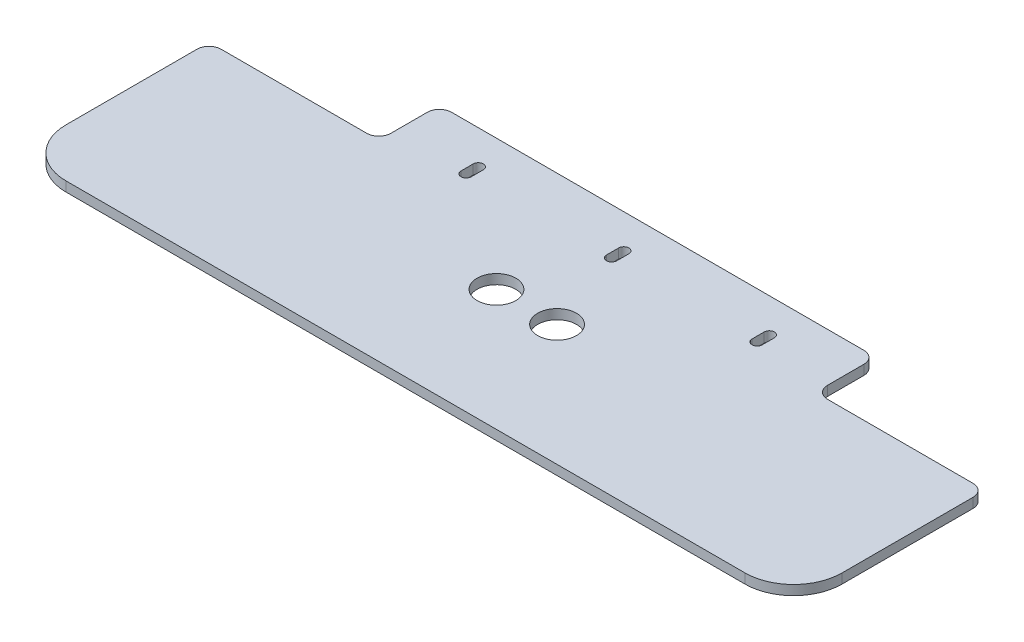
SolidWorks part; units mm, degrees
ref_plane "前视基准面" through (0, 0, 0) normal (0, 0, 1) x (1, 0, 0)
ref_plane "上视基准面" through (0, 0, 0) normal (0, 1, 0) x (1, 0, 0)
ref_plane "右视基准面" through (0, 0, 0) normal (1, 0, 0) x (0, 0, -1)
other "Configuration Table"
sketch "草图1" plane through (0, 0, 0) normal (0, 1, 0) x (1, 0, 0)
  line L0 (90, 54) -> (90, 29)
  line L1 (-160, -50) -> (160, -50)
  line L2 (-160, -50) -> (-160, 29)
  line L3 (-90, 54) -> (90, 54)
  line L4 (160, -50) -> (160, 29)
  line L5 (-160, -50) -> (160, 50) construction
  line L6 (-160, 50) -> (160, -50) construction
  line L7 (90, 29) -> (160, 29)
  line L8 (0, 0) -> (0, 54) construction
  line L9 (-90, 29) -> (-160, 29)
  line L10 (-90, 54) -> (-90, 29)
  point P0 (0, 0)
  dimension "D1" = 320
  dimension "D2" = 100
  dimension "D3" = 180
  dimension "D4" = 25
  dimension "D9" = 25
  dimension "D10" = 70
  dimension "D11" = 104
extrude "凸台-拉伸1" add sketch "草图1" along normal blind 4
fillet "圆角1" radius 5 4 edges at (-90, 2, -29) (-90, 2, -54) (90, 2, -29) (90, 2, -54)
fillet "圆角2" radius 20 2 edges at (160, 2, 50) (-160, 2, 50)
fillet "圆角3" radius 5 2 edges at (-160, 2, -29) (160, 2, -29)
sketch "草图2" plane through (0, 0, 0) normal (0, -1, 0) x (1, 0, 0)
  line L0 (-12.5, -0.0079) -> (12.5, 0.0079) construction
  circle A2 centre (12.5, 0.0079) radius 8
  circle A3 centre (-12.5, -0.0079) radius 8
  point P3 (0, 0)
  dimension "D1" = 16
  dimension "D2" = 25
  dimension "D3" = 16
extrude "切除-拉伸1" cut sketch "草图2" against normal blind 10
sketch "草图4" plane through (0, 4, 0) normal (0, 1, 0) x (1, 0, 0)
  line L0 (0, 35) -> (0, 40) construction
  line L1 (-2.1, 35) -> (-2.1, 40)
  line L2 (2.1, 35) -> (2.1, 40)
  line L7 (62.1, 35) -> (62.1, 40)
  line L8 (57.9, 35) -> (57.9, 40)
  line L9 (60, 35) -> (60, 40) construction
  line L13 (-57.9, 35) -> (-57.9, 40)
  line L14 (-62.1, 35) -> (-62.1, 40)
  line L15 (-60, 35) -> (-60, 40) construction
  line L16 (85, 54) -> (-85, 54) construction
  line L17 (-32.1, 35) -> (-32.1, 40) [skipped]
  line L18 (-27.9, 35) -> (-27.9, 40) [skipped]
  line L19 (27.9, 35) -> (27.9, 40) [skipped]
  line L20 (32.1, 35) -> (32.1, 40) [skipped]
  arc A0 (-2.1, 35) -> (2.1, 35) centre (0, 35) ccw
  arc A1 (2.1, 40) -> (-2.1, 40) centre (0, 40) ccw
  arc A4 (57.9, 35) -> (62.1, 35) centre (60, 35) ccw
  arc A5 (62.1, 40) -> (57.9, 40) centre (60, 40) ccw
  arc A8 (-62.1, 35) -> (-57.9, 35) centre (-60, 35) ccw
  arc A9 (-57.9, 40) -> (-62.1, 40) centre (-60, 40) ccw
  arc A10 (-32.1, 35) -> (-27.9, 35) centre (-30, 35) ccw [skipped]
  arc A11 (-27.9, 40) -> (-32.1, 40) centre (-30, 40) ccw [skipped]
  arc A12 (27.9, 35) -> (32.1, 35) centre (30, 35) ccw [skipped]
  arc A13 (32.1, 40) -> (27.9, 40) centre (30, 40) ccw [skipped]
  point P2 (0, 37.5)
  point P21 (60, 37.5)
  point P34 (-60, 37.5)
  dimension "D3" = 2.1
  dimension "D1" = 14
  dimension "D2" = 5
  dimension "D4" = 3
  dimension "D5" = 3
extrude "切除-拉伸2" cut sketch "草图4" against normal blind 10
